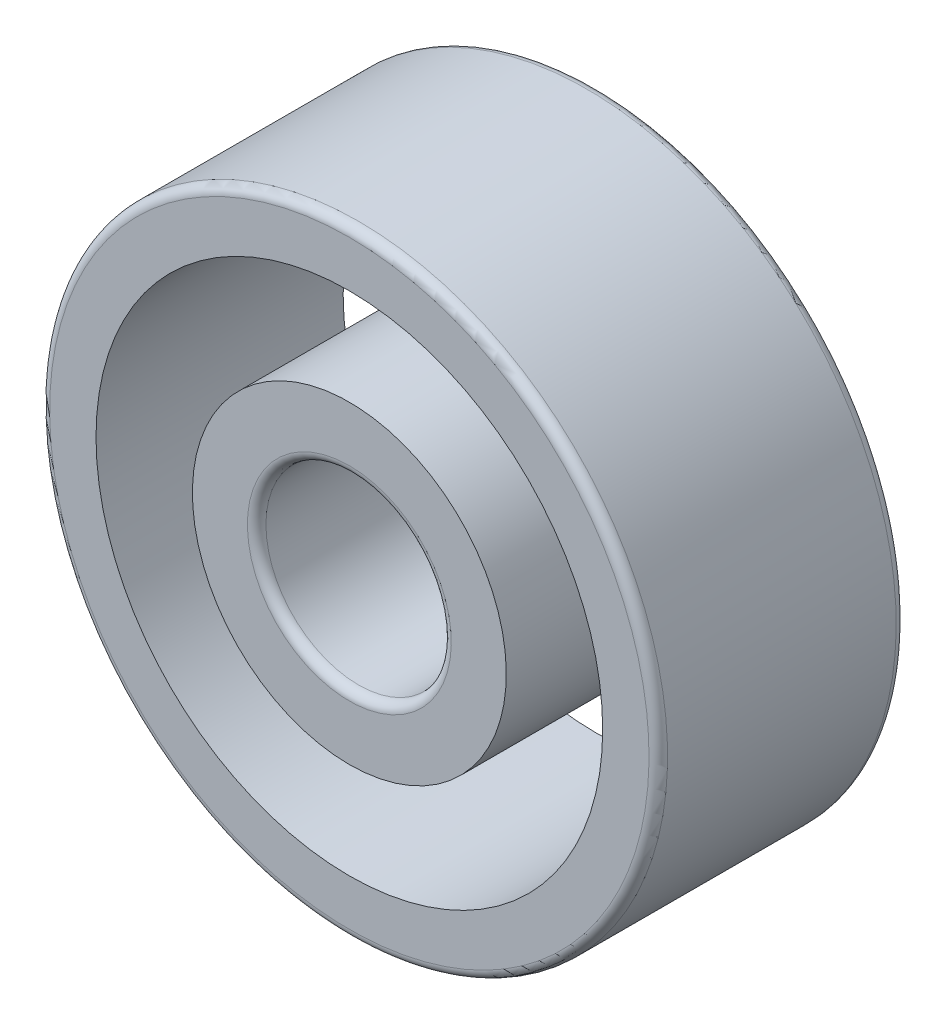
SolidWorks part; units mm, degrees
ref_plane "Front Plane" through (0, 0, 0) normal (0, 0, 1) x (1, 0, 0)
ref_plane "Top Plane" through (0, 0, 0) normal (0, 1, 0) x (1, 0, 0)
ref_plane "Right Plane" through (0, 0, 0) normal (1, 0, 0) x (0, 0, -1)
sketch "Sketch1" plane through (0, 0, 0) normal (1, 0, 0) x (0, 0, -1)
  line L0 (-2, 0) -> (2, 0) construction
  line L1 (-2, 5) -> (-2, 0) construction
  line L2 (-2, 5) -> (2, 5)
  line L3 (-2, 5) -> (-2, 4.1)
  line L4 (-2, 4.1) -> (2, 4.1)
  line L5 (2, 5) -> (2, 4.1)
  line L6 (-2, 2.54) -> (2, 2.54)
  line L7 (-2, 2.54) -> (-2, 1.5)
  line L8 (-2, 1.5) -> (2, 1.5)
  line L9 (2, 2.54) -> (2, 1.5)
  line L10 (2, 5) -> (2, 0) construction
  point P3 (0, 0)
  dimension "D1" = 3
  dimension "D2" = 10
  dimension "D3" = 5.08
  dimension "D4" = 4
  dimension "D5" = 4
  dimension "D6" = 8.2
revolve "Revolve1" add sketch "Sketch1" angle 360 about L0
fillet "Fillet1" radius 0.15 2 edges at (0, -5, -2) (0, -5, 2)
fillet "Fillet2" radius 0.15 2 edges at (0, -1.5, -2) (0, -1.5, 2)
